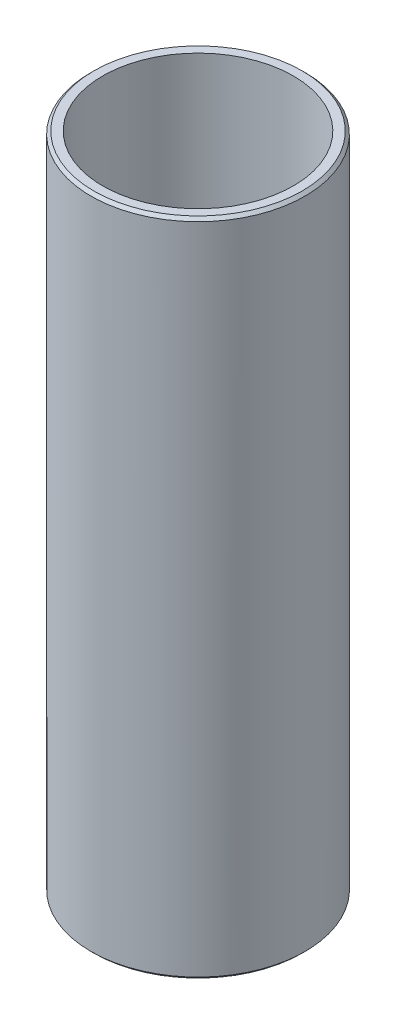
SolidWorks part; units mm, degrees
material "ABS"
ref_plane "Front Plane" through (0, 0, 0) normal (0, 0, 1) x (1, 0, 0)
ref_plane "Top Plane" through (0, 0, 0) normal (0, 1, 0) x (1, 0, 0)
ref_plane "Right Plane" through (0, 0, 0) normal (1, 0, 0) x (0, 0, -1)
sketch "Sketch1" plane through (0, 0, 0) normal (0, 1, 0) x (1, 0, 0)
  circle A0 centre (0, 0) radius 7.3
  circle A1 centre (0, 0) radius 6.5
  dimension "D1" = 14.6
  dimension "D2" = 13
extrude "Boss-Extrude1" add sketch "Sketch1" along normal blind 45
chamfer "Chamfer1" distance 0.2 angle 45 2 edges at (0, 45, 7.3) (0, 0, 7.3)
